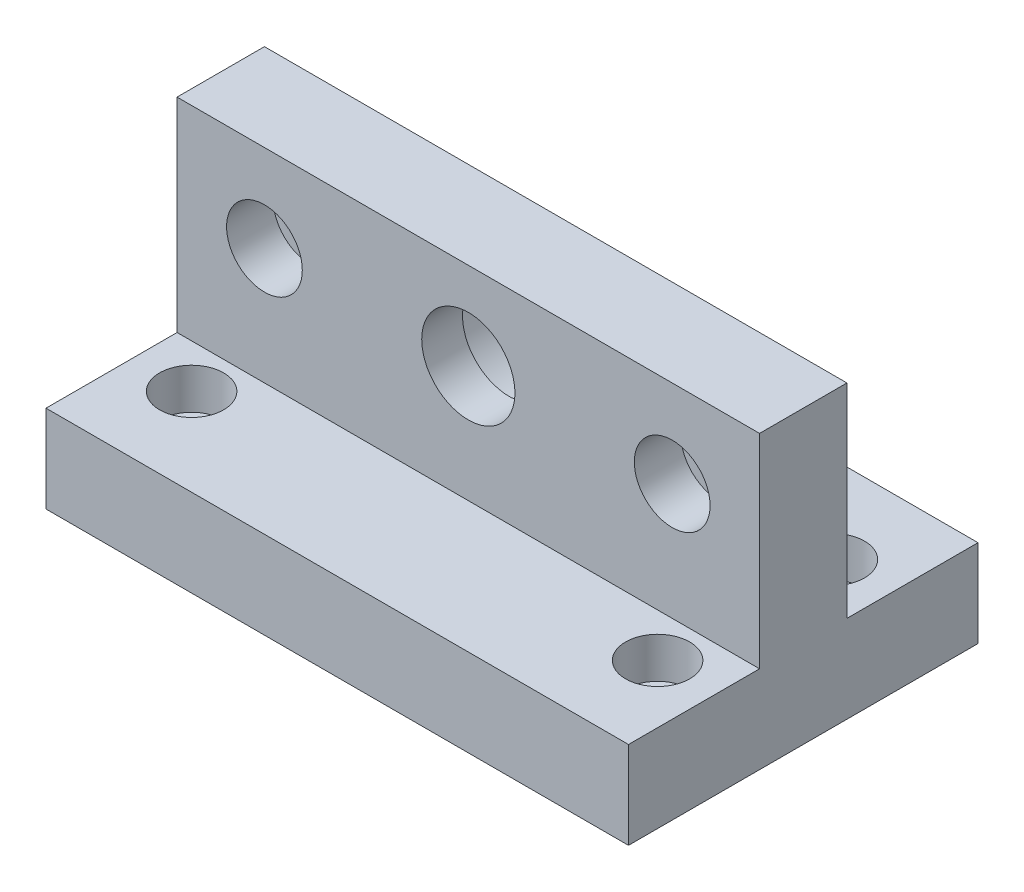
SolidWorks part; units mm, degrees
ref_plane "前视基准面" through (0, 0, 0) normal (0, 0, 1) x (1, 0, 0)
ref_plane "上视基准面" through (0, 0, 0) normal (0, 1, 0) x (1, 0, 0)
ref_plane "右视基准面" through (0, 0, 0) normal (1, 0, 0) x (0, 0, -1)
sketch "草图1" plane through (0, 0, 0) normal (0, 0, 1) x (1, 0, 0)
  line L1 (0, 0) -> (100, 0)
  line L2 (0, 0) -> (0, 35)
  line L3 (0, 35) -> (100, 35)
  line L4 (100, 0) -> (100, 35)
  dimension "D1" = 100
  dimension "D2" = 35
extrude "凸台-拉伸1" add sketch "草图1" along normal blind 15
sketch "草图2" plane through (0, 0, 0) normal (0, -1, 0) x (1, 0, 0)
  line L0 (0, 15) -> (100, 15) construction
  line L1 (0, 37.5) -> (100, 37.5)
  line L2 (0, 37.5) -> (0, -22.5)
  line L3 (0, -22.5) -> (100, -22.5)
  line L4 (100, 37.5) -> (100, -22.5)
  dimension "D1" = 60
  dimension "D2" = 22.5
  dimension "D3" = 100
extrude "凸台-拉伸2" add sketch "草图2" along normal blind 15
sketch "草图3" plane through (0, 0, 0) normal (0, 1, 0) x (1, 0, 0)
  line L0 (0, 22.5) -> (100, 22.5) construction
  line L1 (0, 0) -> (0, 22.5) construction
  line L2 (100, 22.5) -> (100, 0) construction
  line L3 (-7.6216, -7.5) -> (109.5031, -7.5) construction
  circle A0 centre (10, 7.5) radius 3.5
  circle A1 centre (90, 7.5) radius 3.5
  circle A2 centre (90, -22.5) radius 3.5
  circle A3 centre (10, -22.5) radius 3.5
  dimension "D1" = 7
  dimension "D2" = 7
  dimension "D3" = 15
  dimension "D4" = 15
  dimension "D5" = 10
  dimension "D6" = 10
extrude "切除-拉伸1" cut sketch "草图3" against normal through all
sketch "草图4" plane through (0, 0, 0) normal (0, 1, 0) x (1, 0, 0)
  circle A0 centre (10, 7.5) radius 5.5
  circle A1 centre (90, 7.5) radius 5.5
  circle A2 centre (10, -22.5) radius 5.5
  circle A3 centre (90, -22.5) radius 5.5
  dimension "D1" = 11
  dimension "D2" = 11
  dimension "D3" = 11
  dimension "D4" = 11
extrude "切除-拉伸2" cut sketch "草图4" against normal blind 7
sketch "草图5" plane through (0, 0, 0) normal (0, 0, -1) x (-1, 0, 0)
  line L0 (-100, 0) -> (-100, 35) construction
  line L1 (0, 35) -> (0, 0) construction
  line L2 (-100, 35) -> (0, 35) construction
  circle A0 centre (-85, 20) radius 4.5
  circle A1 centre (-15, 20) radius 4.5
  circle A2 centre (-50, 20) radius 8
  dimension "D1" = 9
  dimension "D2" = 9
  dimension "D3" = 16
  dimension "D4" = 15
  dimension "D5" = 15
  dimension "D6" = 35
  dimension "D7" = 15
  dimension "D8" = 15
  dimension "D9" = 15
extrude "切除-拉伸3" cut sketch "草图5" against normal through all
sketch "草图6" plane through (0, 0, 0) normal (0, 0, -1) x (-1, 0, 0)
  circle A0 centre (-50, 20) radius 12
  dimension "D1" = 24
extrude "切除-拉伸4" cut sketch "草图6" against normal blind 8
sketch "草图7" plane through (0, 0, 15) normal (0, 0, 1) x (1, 0, 0)
  circle A0 centre (15, 20) radius 6.5
  circle A1 centre (85, 20) radius 6.5
  dimension "D1" = 13
  dimension "D2" = 13
extrude "切除-拉伸5" cut sketch "草图7" against normal blind 8
